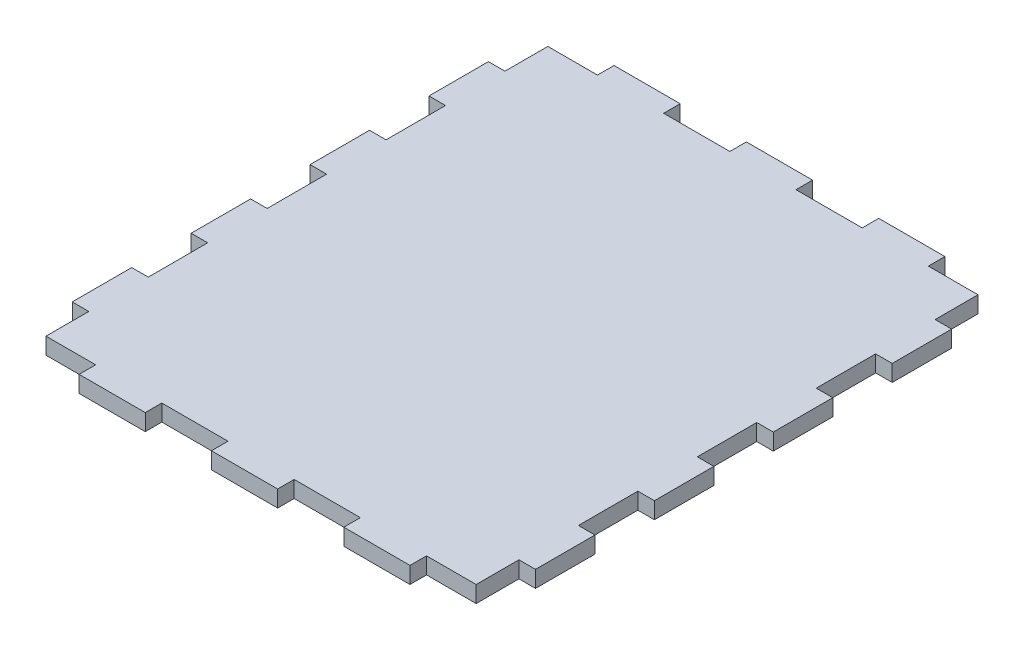
SolidWorks part; units mm, degrees
material "Balsa"
ref_plane "Front" through (0, 0, 0) normal (0, 0, 1) x (1, 0, 0)
ref_plane "Top" through (0, 0, 0) normal (0, 1, 0) x (1, 0, 0)
ref_plane "Right" through (0, 0, 0) normal (1, 0, 0) x (0, 0, -1)
sketch "Esboço1" plane through (0, 0, 0) normal (0, 1, 0) x (1, 0, 0)
  line L1 (-42, -48.5) -> (42, -48.5)
  line L2 (-42, -48.5) -> (-42, 48.5)
  line L3 (-42, 48.5) -> (42, 48.5)
  line L4 (42, -48.5) -> (42, 48.5)
  line L5 (-42, -48.5) -> (42, 48.5) construction
  line L6 (-42, 48.5) -> (42, -48.5) construction
  point P0 (0, 0)
  dimension "D1" = 84
  dimension "D2" = 97
extrude "Ressalto-extrusão1" add sketch "Esboço1" along normal blind 3
sketch "Esboço2" plane through (0, 0, 0) normal (0, -1, 0) x (1, 0, 0)
  line L1 (-42, -48.5) -> (-39, -48.5)
  line L2 (-42, -48.5) -> (-42, -37.7222)
  line L3 (-42, -37.7222) -> (-39, -37.7222)
  line L4 (-39, -48.5) -> (-39, -37.7222)
  line L6 (39, -48.5) -> (42, -48.5)
  line L7 (39, -48.5) -> (39, -37.7222)
  line L8 (39, -37.7222) -> (42, -37.7222)
  line L9 (42, -48.5) -> (42, -37.7222)
  line L10 (39, -26.94) -> (42, -26.94)
  line L11 (39, -26.94) -> (39, -16.1622)
  line L12 (39, -16.1622) -> (42, -16.1622)
  line L13 (42, -26.94) -> (42, -16.1622)
  line L14 (39, -5.38) -> (42, -5.38)
  line L15 (39, -5.38) -> (39, 5.3978)
  line L16 (39, 5.3978) -> (42, 5.3978)
  line L17 (42, -5.38) -> (42, 5.3978)
  line L18 (39, 16.18) -> (42, 16.18)
  line L19 (39, 16.18) -> (39, 26.9578)
  line L20 (39, 26.9578) -> (42, 26.9578)
  line L21 (42, 16.18) -> (42, 26.9578)
  line L22 (39, 37.74) -> (42, 37.74)
  line L23 (39, 37.74) -> (39, 48.5178)
  line L24 (39, 48.5178) -> (42, 48.5178)
  line L25 (42, 37.74) -> (42, 48.5178)
  line L26 (-42, -26.94) -> (-39, -26.94)
  line L27 (-42, -26.94) -> (-42, -16.1622)
  line L28 (-42, -16.1622) -> (-39, -16.1622)
  line L29 (-39, -26.94) -> (-39, -16.1622)
  line L30 (-42, -5.38) -> (-39, -5.38)
  line L31 (-42, -5.38) -> (-42, 5.3978)
  line L32 (-42, 5.3978) -> (-39, 5.3978)
  line L33 (-39, -5.38) -> (-39, 5.3978)
  line L34 (-42, 16.18) -> (-39, 16.18)
  line L35 (-42, 16.18) -> (-42, 26.9578)
  line L36 (-42, 26.9578) -> (-39, 26.9578)
  line L37 (-39, 16.18) -> (-39, 26.9578)
  line L38 (-42, 37.74) -> (-39, 37.74)
  line L39 (-42, 37.74) -> (-42, 48.5178)
  line L40 (-42, 48.5178) -> (-39, 48.5178)
  line L41 (-39, 37.74) -> (-39, 48.5178)
  dimension "D1" = 3
  dimension "D2" = 10.7778
  dimension "D3" = 2
  dimension "D4" = 5
extrude "Corte-extrusão4" cut sketch "Esboço2" against normal blind 3
sketch "Esboço5" plane through (0, 0, 0) normal (0, 1, 0) x (1, 0, 0)
  line L0 (-42, 45.5) -> (-42, 48.5)
  line L1 (-42, -48.5) -> (-30, -48.5)
  line L2 (-42, -48.5) -> (-42, -45.5)
  line L3 (-42, 48.5) -> (-30, 48.5)
  line L4 (42, -48.5) -> (42, -45.5)
  line L8 (42, 45.5) -> (42, 48.5)
  line L9 (-42, -45.5) -> (-30, -45.5)
  line L10 (-30, -48.5) -> (-30, -45.5)
  line L11 (-18, -48.5) -> (-18, -45.5)
  line L12 (-18, -45.5) -> (-6, -45.5)
  line L13 (-6, -48.5) -> (-6, -45.5)
  line L14 (30, -48.5) -> (42, -48.5)
  line L15 (6, -48.5) -> (6, -45.5)
  line L16 (6, -45.5) -> (18, -45.5)
  line L17 (18, -48.5) -> (18, -45.5)
  line L18 (6, -48.5) -> (18, -48.5)
  line L19 (30, -48.5) -> (30, -45.5)
  line L20 (30, -45.5) -> (42, -45.5)
  line L21 (-18, -48.5) -> (-6, -48.5)
  line L22 (-18, 45.5) -> (-6, 45.5)
  line L23 (-18, 45.5) -> (-18, 48.5)
  line L24 (-18, 48.5) -> (-6, 48.5)
  line L25 (-6, 45.5) -> (-6, 48.5)
  line L26 (6, 45.5) -> (18, 45.5)
  line L27 (6, 45.5) -> (6, 48.5)
  line L28 (6, 48.5) -> (18, 48.5)
  line L29 (18, 45.5) -> (18, 48.5)
  line L30 (30, 45.5) -> (42, 45.5)
  line L31 (30, 45.5) -> (30, 48.5)
  line L32 (30, 48.5) -> (42, 48.5)
  line L34 (-42, 45.5) -> (-30, 45.5)
  line L37 (-30, 45.5) -> (-30, 48.5)
  line L42 (-42, 48.5) -> (-30, 48.5) [skipped]
  line L43 (30, 48.5) -> (42, 48.5) [skipped]
  line L44 (6, 48.5) -> (18, 48.5) [skipped]
  line L45 (-18, 48.5) -> (-6, 48.5) [skipped]
  line L46 (42, 45.5) -> (42, 48.5) [skipped]
  line L47 (42, -48.5) -> (42, -45.5) [skipped]
  point P0 (0, 0)
  dimension "D1" = 84
  dimension "D2" = 97
  dimension "D3" = 3
  dimension "D4" = 12
  dimension "D5" = 4
  dimension "D6" = 2
extrude "Corte-extrusão9" cut sketch "Esboço5" along normal up to next
